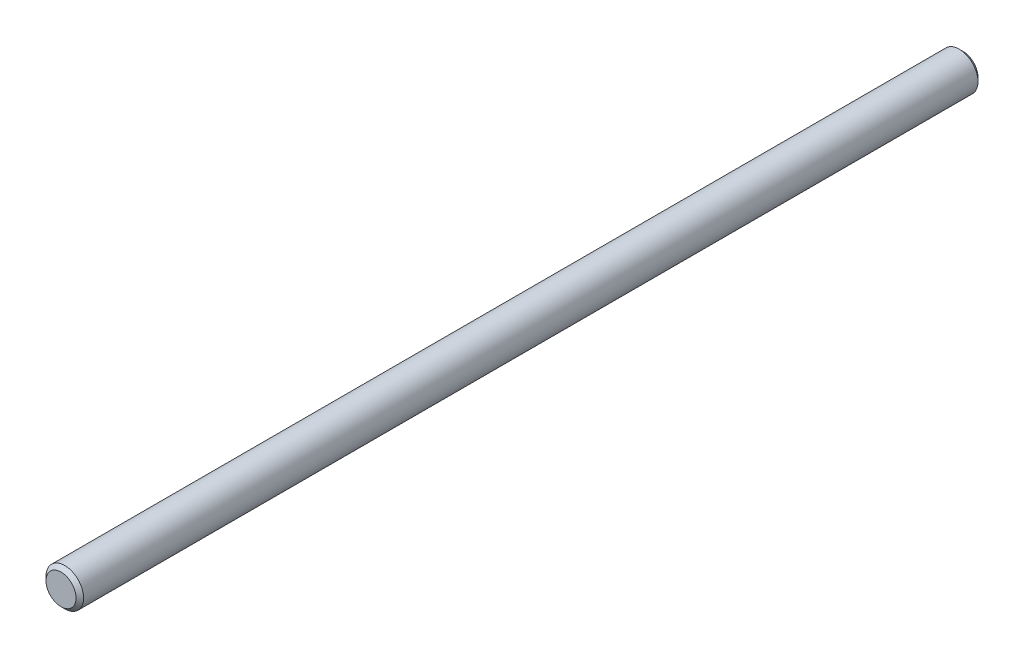
SolidWorks part; units mm, degrees
ref_plane "Front" through (0, 0, 0) normal (0, 0, 1) x (1, 0, 0)
ref_plane "Top" through (0, 0, 0) normal (0, 1, 0) x (1, 0, 0)
ref_plane "Right" through (0, 0, 0) normal (1, 0, 0) x (0, 0, -1)
sketch "Sketch1" plane through (0, 0, 0) normal (0, 0, 1) x (1, 0, 0)
  circle A0 centre (0, 0) radius 1.5875
  dimension "dia" = 3.175
sketch "Sketch2" plane through (0, 0, 0) normal (1, 0, 0) x (0, 0, -1)
  line L0 (-38.1, 0) -> (38.1, 0) construction
  line L1 (5.2388, 0) -> (-5.2388, 0) construction
  line L3 (38.1, 1.5875) -> (38.1, -1.5875) construction
  line L4 (-38.1, 1.5875) -> (-38.1, -1.5875) construction
  line L5 (-19.05, 1.5875) -> (-19.05, -1.5875) construction
  line L6 (19.05, 1.5875) -> (19.05, -1.5875) construction
  point P6 (0, 0)
  point P10 (38.1, 0)
  point P13 (-38.1, 0)
  point P16 (-19.05, 0)
  point P19 (19.05, 0)
  dimension "D1" = 3.175
  dimension "lg" = 76.2
  dimension "D2" = 19.05
  dimension "D3" = 19.05
sketch "Sketch3" plane through (0, 0, 0) normal (0, 0, 1) x (1, 0, 0)
  line L0 (0, 1.5875) -> (0, -1.5875) construction
  circle A0 centre (0, 0) radius 1.5875
  dimension "D1" = 3.175
extrude "Boss-Extrude1" add sketch "Sketch3" along normal mid plane 76.2
chamfer "Chamfer1" distance 0.3175 angle 45 2 edges at (1.5875, 0, -38.1) (1.5875, 0, 38.1)
equation "\"D1@Sketch2\"=\"dia@sketch1\""
equation "\"D1@Sketch3\"=\"dia@Sketch1\""
equation "\"D1@Boss-Extrude1\"=\"lg@Sketch2\""
equation "\"D1@Chamfer1\"=\"dia@Sketch1\"*.1"
